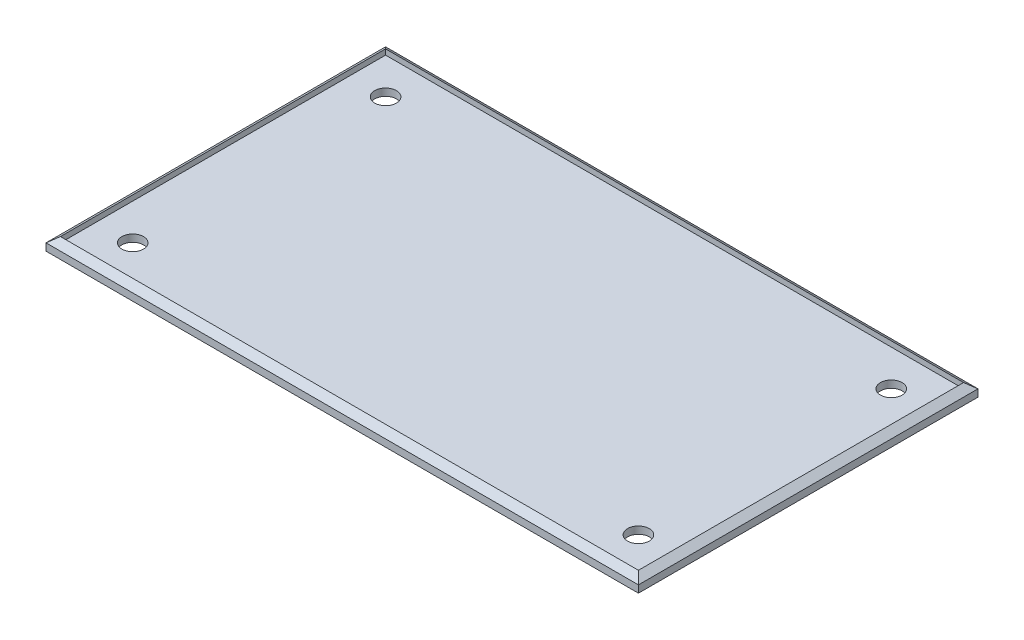
SolidWorks part; units mm, degrees
ref_plane "Front Plane" through (0, 0, 0) normal (0, 0, 1) x (1, 0, 0)
ref_plane "Top Plane" through (0, 0, 0) normal (0, 1, 0) x (1, 0, 0)
ref_plane "Right Plane" through (0, 0, 0) normal (1, 0, 0) x (0, 0, -1)
sketch "Sketch1" plane through (0, 0, 0) normal (0, 1, 0) x (1, 0, 0)
  line L1 (-80, 45) -> (80, 45)
  line L2 (-80, 45) -> (-80, -45)
  line L3 (-80, -45) -> (80, -45)
  line L4 (80, 45) -> (80, -45)
  line L5 (-80, 45) -> (80, -45) construction
  line L6 (-80, -45) -> (80, 45) construction
  point P0 (0, 0)
  dimension "D1" = 160
  dimension "D2" = 90
extrude "Boss-Extrude1" add sketch "Sketch1" along normal blind 2
sketch "Sketch2" plane through (0, 0, 45) normal (0, 0, 1) x (1, 0, 0)
  line L0 (-82, 0) -> (-80, 0)
  line L1 (80, 0) -> (82, 0)
  line L2 (80, 0) -> (80, 3.5)
  line L4 (82, 0) -> (82, 2)
  line L5 (-82, 0) -> (-82, 2)
  line L7 (-80, 0) -> (-80, 3.5)
  line L8 (-80, 2) -> (-82, 2) construction
  line L9 (-82, 2) -> (-80, 3.5)
  line L10 (80, 2) -> (82, 2) construction
  line L11 (82, 2) -> (80, 3.5)
  dimension "D1" = 2
  dimension "D3" = 2
extrude "Boss-Extrude2" add sketch "Sketch2" against normal blind 90
sketch "Sketch3" plane through (-82, 0, 0) normal (-1, 0, 0) x (0, 0, 1)
  line L0 (-47, 0) -> (-45, 0)
  line L1 (-47, 0) -> (-47, 2)
  line L2 (-45, 0) -> (-45, 3.5)
  line L3 (-47, 2) -> (-45, 3.5)
  line L8 (45, 0) -> (45, 3.5)
  line L10 (47, 2) -> (45, 3.5)
  line L11 (47, 0) -> (47, 2)
  line L12 (47, 0) -> (45, 0)
  point P4 (0, 0)
  point P6 (0, 0)
  dimension "D1" = 2
  dimension "D2" = 2.5
  dimension "D3" = 2.5
  dimension "D4" = 2
extrude "Boss-Extrude5" add sketch "Sketch3" against normal blind 164
sketch "Sketch4" plane through (0, 0, -45) normal (0, 0, 1) x (1, 0, 0)
  line L0 (-80, 3.5) -> (-82, 2)
  line L1 (-82, 2) -> (-82, 3.5)
  line L2 (-82, 3.5) -> (-80, 3.5)
  line L3 (80, 3.5) -> (82, 3.5)
  line L4 (82, 3.5) -> (82, 2)
  line L5 (82, 2) -> (80, 3.5)
extrude "Cut-Extrude1" cut sketch "Sketch4" against normal blind 164 and the other way blind 164
sketch "Sketch5" plane through (0, 2, 0) normal (0, 1, 0) x (1, 0, 0)
  line L1 (-80, 45) -> (-70, 45) construction
  line L2 (-80, 45) -> (-80, 35) construction
  line L3 (-80, 35) -> (-70, 35) construction
  line L4 (-70, 45) -> (-70, 35) construction
  line L5 (80, 45) -> (70, 45) construction
  line L6 (80, 45) -> (80, 35) construction
  line L7 (80, 35) -> (70, 35) construction
  line L8 (70, 45) -> (70, 35) construction
  line L9 (80, -45) -> (70, -45) construction
  line L10 (80, -45) -> (80, -35) construction
  line L11 (80, -35) -> (70, -35) construction
  line L12 (70, -45) -> (70, -35) construction
  line L13 (-70, -35) -> (-80, -35) construction
  line L14 (-70, -35) -> (-70, -45) construction
  line L15 (-70, -45) -> (-80, -45) construction
  line L16 (-80, -35) -> (-80, -45) construction
  circle A0 centre (-70, 35) radius 3
  circle A1 centre (70, 35) radius 3
  circle A2 centre (70, -35) radius 3
  circle A3 centre (-70, -35) radius 3
  dimension "D1" = 10
  dimension "D2" = 10
  dimension "D3" = 10
  dimension "D4" = 10
  dimension "D5" = 10
  dimension "D6" = 10
  dimension "D7" = 10
  dimension "D8" = 10
extrude "Cut-Extrude2" cut sketch "Sketch5" against normal blind 164
sketch "Sketch6" plane through (0, 2, 0) normal (0, 1, 0) x (1, 0, 0)
  line L0 (-70, 35) -> (70, 35) construction
  line L1 (70, 35) -> (70, -35) construction
  line L2 (70, -35) -> (-70, -35) construction
  line L3 (-70, -35) -> (-70, 35) construction
  line L4 (-80, 45) -> (80, 45) construction
  line L5 (80, 45) -> (80, -45) construction
  line L6 (80, -45) -> (80, 45) construction
  line L7 (80, 45) -> (80, -45) construction
  line L8 (80, -45) -> (-80, -45) construction
  line L9 (-80, -45) -> (-80, 45) construction
  line L10 (-80, 45) -> (80, -45) construction
  line L11 (-80, -45) -> (80, 45) construction
